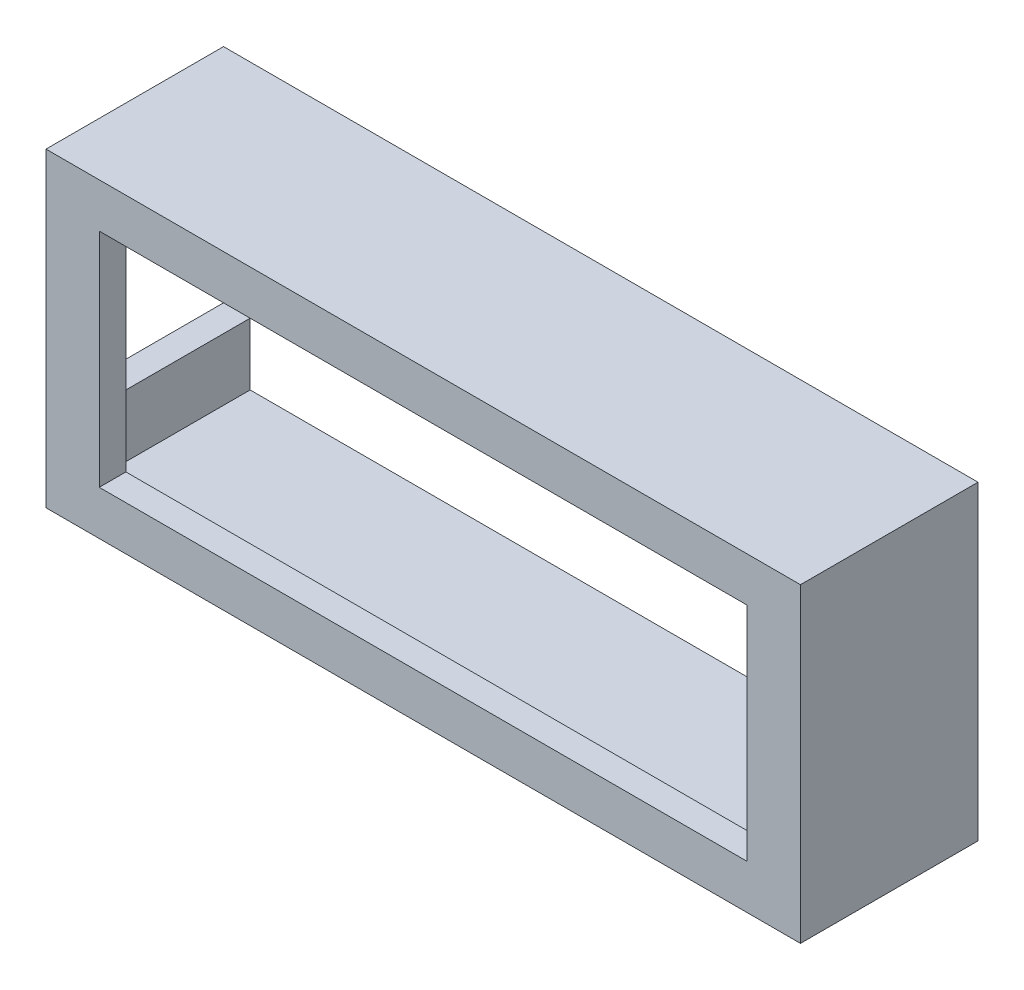
SolidWorks part; units mm, degrees
ref_plane "Front Plane" through (0, 0, 0) normal (0, 0, 1) x (1, 0, 0)
ref_plane "Top Plane" through (0, 0, 0) normal (0, 1, 0) x (1, 0, 0)
ref_plane "Right Plane" through (0, 0, 0) normal (1, 0, 0) x (0, 0, -1)
sketch "Sketch1" plane through (0, 0, 0) normal (0, 0, 1) x (1, 0, 0)
  line L1 (-42.5, 17.5) -> (42.5, 17.5)
  line L2 (-42.5, 17.5) -> (-42.5, -17.5)
  line L3 (-42.5, -17.5) -> (42.5, -17.5)
  line L4 (42.5, 17.5) -> (42.5, -17.5)
  line L5 (-42.5, 17.5) -> (42.5, -17.5) construction
  line L6 (-42.5, -17.5) -> (42.5, 17.5) construction
  point P0 (0, 0)
  dimension "D1" = 85
  dimension "D2" = 35
extrude "Boss-Extrude1" add sketch "Sketch1" along normal blind 20
shell "Shell1" thickness 3
sketch "Sketch3" plane through (-42.5, 0, 0) normal (-1, 0, 0) x (0, 0, 1)
  line L0 (0, 17.5) -> (0, -17.5) construction
  line L1 (0, 7.5) -> (17, 7.5)
  line L2 (0, 7.5) -> (0, -7.5)
  line L3 (0, -7.5) -> (17, -7.5)
  line L4 (17, 7.5) -> (17, -7.5)
  line L5 (20, 17.5) -> (0, 17.5) construction
  line L6 (20, -17.5) -> (0, -17.5) construction
  line L7 (20, 17.5) -> (20, -17.5) construction
  dimension "D1" = 10
  dimension "D2" = 10
  dimension "D3" = 3
extrude "Cut-Extrude1" cut sketch "Sketch3" against normal blind 20
sketch "Sketch4" plane through (0, 0, 20) normal (0, 0, 1) x (1, 0, 0)
  line L0 (42.5, 17.5) -> (-42.5, 17.5) construction
  line L1 (-36.5, 12.5) -> (36.5, 12.5)
  line L2 (-36.5, 12.5) -> (-36.5, -12.5)
  line L3 (-36.5, -12.5) -> (36.5, -12.5)
  line L4 (36.5, 12.5) -> (36.5, -12.5)
  line L5 (-36.5, 12.5) -> (36.5, -12.5) construction
  line L6 (-36.5, -12.5) -> (36.5, 12.5) construction
  line L8 (42.5, -17.5) -> (42.5, 17.5) construction
  point P0 (0, 0)
  dimension "D1" = 5
  dimension "D2" = 6
extrude "Cut-Extrude2" cut sketch "Sketch4" against normal blind 20
